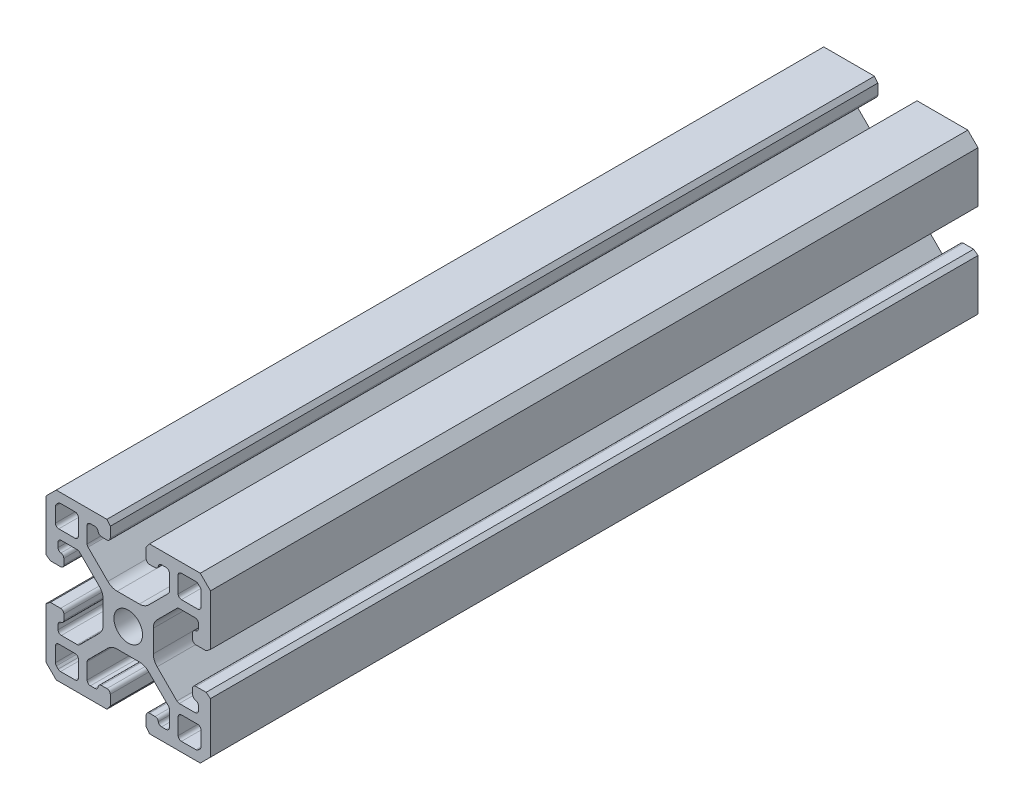
SolidWorks part; units mm, degrees
material "6063-T6"
ref_plane "Front Plane" through (0, 0, 0) normal (0, 0, 1) x (1, 0, 0)
ref_plane "Top Plane" through (0, 0, 0) normal (0, 1, 0) x (1, 0, 0)
ref_plane "Right Plane" through (0, 0, 0) normal (1, 0, 0) x (0, 0, -1)
sketch "Sketch1" plane through (0, 0, 0) normal (0, 0, 1) x (-1, 0, 0)
  line L0 (19.05, 0) -> (-19.05, 0) construction
  line L1 (0, -19.05) -> (0, 19.05) construction
  line L2 (-19.05, 4.9276) -> (-19.05, 16.6878)
  line L3 (-18.044, 4.1656) -> (-19.05, 4.9276)
  line L4 (-15.6692, 4.1656) -> (-18.044, 4.1656)
  line L5 (-14.9297, 6.2238) -> (-14.9074, 4.9409)
  line L6 (-16.256, 8.763) -> (-16.256, 7.7216)
  line L7 (-16.256, -7.7216) -> (-16.256, -8.763)
  line L8 (-14.9074, -4.9409) -> (-14.9297, -6.2238)
  line L9 (-18.044, -4.1656) -> (-15.6692, -4.1656)
  line L10 (-19.05, -4.9276) -> (-18.044, -4.1656)
  line L11 (-19.05, -16.6878) -> (-19.05, -4.9276)
  line L26 (-16.8656, 12.319) -> (-16.8656, 15.6829)
  line L27 (-16.6424, 16.2217) -> (-16.2217, 16.6424)
  line L28 (-15.6829, 16.8656) -> (-12.319, 16.8656)
  line L29 (-11.557, 16.1036) -> (-11.557, 12.319)
  line L30 (-12.319, 11.557) -> (-16.1036, 11.557)
  line L31 (-6.7001, -4.7245) -> (-11.2775, -9.3018)
  line L32 (-11.8163, -9.525) -> (-15.494, -9.525)
  line L34 (-15.494, 9.525) -> (-11.8163, 9.525)
  line L35 (-11.2775, 9.3018) -> (-6.7001, 4.7245)
  line L36 (-5.8074, 2.5692) -> (-5.8074, -2.5692)
  line L37 (-16.1036, -11.557) -> (-12.319, -11.557)
  line L38 (-11.557, -12.319) -> (-11.557, -16.1036)
  line L39 (-12.319, -16.8656) -> (-15.6829, -16.8656)
  line L40 (-16.2217, -16.6424) -> (-16.6424, -16.2217)
  line L41 (-16.8656, -15.6829) -> (-16.8656, -12.319)
  line L42 (15.6829, -16.8656) -> (12.319, -16.8656)
  line L43 (11.557, -16.1036) -> (11.557, -12.319)
  line L44 (12.319, -11.557) -> (16.1036, -11.557)
  line L45 (16.8656, -12.319) -> (16.8656, -15.6829)
  line L46 (16.6424, -16.2217) -> (16.2217, -16.6424)
  line L47 (11.557, 12.319) -> (11.557, 16.1036)
  line L48 (12.319, 16.8656) -> (15.6829, 16.8656)
  line L49 (16.2217, 16.6424) -> (16.6424, 16.2217)
  line L100 (5.8074, -2.5692) -> (5.8074, 2.5692)
  line L101 (6.7001, 4.7245) -> (11.2775, 9.3018)
  line L102 (11.8163, 9.525) -> (15.494, 9.525)
  line L103 (16.256, 8.763) -> (16.256, 7.7216)
  line L104 (14.9297, 6.2238) -> (14.9074, 4.9409)
  line L105 (15.6692, 4.1656) -> (18.044, 4.1656)
  line L106 (18.044, 4.1656) -> (19.05, 4.9276)
  line L107 (19.05, 4.9276) -> (19.05, 16.6878)
  line L108 (19.05, 16.6878) -> (16.6878, 19.05)
  line L109 (16.6878, 19.05) -> (4.9276, 19.05)
  line L110 (4.9276, 19.05) -> (4.1656, 18.044)
  line L111 (4.1656, 18.044) -> (4.1656, 15.6692)
  line L112 (4.9409, 14.9074) -> (6.2238, 14.9297)
  line L113 (7.7216, 16.256) -> (8.763, 16.256)
  line L114 (9.525, 15.494) -> (9.525, 11.8163)
  line L115 (9.3018, 11.2775) -> (4.7245, 6.7001)
  line L116 (2.5692, 5.8074) -> (-2.5692, 5.8074)
  line L117 (-4.7245, 6.7001) -> (-9.3018, 11.2775)
  line L118 (-9.525, 11.8163) -> (-9.525, 15.494)
  line L119 (-8.763, 16.256) -> (-7.7216, 16.256)
  line L120 (-6.2238, 14.9297) -> (-4.9409, 14.9074)
  line L121 (-4.1656, 15.6692) -> (-4.1656, 18.044)
  line L122 (-4.1656, 18.044) -> (-4.9276, 19.05)
  line L123 (-4.9276, 19.05) -> (-16.6878, 19.05)
  line L124 (-16.6878, 19.05) -> (-19.05, 16.6878)
  line L126 (-19.05, -16.6878) -> (-16.6878, -19.05)
  line L127 (-16.6878, -19.05) -> (-4.9276, -19.05)
  line L128 (-4.9276, -19.05) -> (-4.1656, -18.044)
  line L129 (-4.1656, -18.044) -> (-4.1656, -15.6692)
  line L130 (-4.9409, -14.9074) -> (-6.2238, -14.9297)
  line L131 (-7.7216, -16.256) -> (-8.763, -16.256)
  line L132 (-9.525, -15.494) -> (-9.525, -11.8163)
  line L133 (-9.3018, -11.2775) -> (-4.7245, -6.7001)
  line L134 (-2.5692, -5.8074) -> (2.5692, -5.8074)
  line L135 (4.7245, -6.7001) -> (9.3018, -11.2775)
  line L136 (9.525, -11.8163) -> (9.525, -15.494)
  line L137 (8.763, -16.256) -> (7.7216, -16.256)
  line L138 (6.2238, -14.9297) -> (4.9409, -14.9074)
  line L139 (4.1656, -15.6692) -> (4.1656, -18.044)
  line L140 (4.1656, -18.044) -> (4.9409, -19.05)
  line L141 (4.9409, -19.05) -> (16.6878, -19.05)
  line L142 (16.6878, -19.05) -> (19.05, -16.6878)
  line L143 (19.05, -16.6878) -> (19.05, -4.9276)
  line L144 (19.05, -4.9276) -> (18.044, -4.1656)
  line L145 (18.044, -4.1656) -> (15.6692, -4.1656)
  line L146 (14.9074, -4.9409) -> (14.9297, -6.2238)
  line L147 (16.256, -7.7216) -> (16.256, -8.763)
  line L148 (15.494, -9.525) -> (11.8163, -9.525)
  line L149 (11.2775, -9.3018) -> (6.7001, -4.7245)
  line L150 (16.8656, 15.6829) -> (16.8656, 12.319)
  line L151 (16.1036, 11.557) -> (12.319, 11.557)
  arc A0 (-16.256, 8.763) -> (-15.494, 9.525) centre (-15.494, 8.763) cw
  arc A1 (-14.9074, 4.9409) -> (-15.6692, 4.1656) centre (-15.6692, 4.9276) cw
  arc A2 (-15.5928, 6.966) -> (-14.9297, 6.2238) centre (-15.6916, 6.2105) cw
  arc A3 (-15.5928, 6.966) -> (-16.256, 7.7216) centre (-15.494, 7.7216) cw
  arc A4 (-15.494, -9.525) -> (-16.256, -8.763) centre (-15.494, -8.763) cw
  arc A5 (-16.256, -7.7216) -> (-15.5928, -6.966) centre (-15.494, -7.7216) cw
  arc A6 (-14.9297, -6.2238) -> (-15.5928, -6.966) centre (-15.6916, -6.2105) cw
  arc A7 (-15.6692, -4.1656) -> (-14.9074, -4.9409) centre (-15.6692, -4.9276) cw
  arc A27 (-16.6424, 16.2217) -> (-16.8656, 15.6829) centre (-16.1036, 15.6829) ccw
  arc A28 (-15.6829, 16.8656) -> (-16.2217, 16.6424) centre (-15.6829, 16.1036) ccw
  arc A29 (-11.557, 16.1036) -> (-12.319, 16.8656) centre (-12.319, 16.1036) ccw
  arc A30 (-12.319, 11.557) -> (-11.557, 12.319) centre (-12.319, 12.319) ccw
  arc A31 (-16.8656, 12.319) -> (-16.1036, 11.557) centre (-16.1036, 12.319) ccw
  arc A32 (-11.8163, -9.525) -> (-11.2775, -9.3018) centre (-11.8163, -8.763) ccw
  arc A35 (-11.2775, 9.3018) -> (-11.8163, 9.525) centre (-11.8163, 8.763) ccw
  arc A72 (5.8074, -2.5692) -> (6.7001, -4.7245) centre (8.8554, -2.5692) ccw
  arc A73 (6.7001, 4.7245) -> (5.8074, 2.5692) centre (8.8554, 2.5692) ccw
  arc A74 (11.8163, 9.525) -> (11.2775, 9.3018) centre (11.8163, 8.763) ccw
  arc A75 (16.256, 8.763) -> (15.494, 9.525) centre (15.494, 8.763) ccw
  arc A76 (15.5928, 6.966) -> (16.256, 7.7216) centre (15.494, 7.7216) ccw
  arc A77 (15.5928, 6.966) -> (14.9297, 6.2238) centre (15.6916, 6.2105) ccw
  arc A78 (14.9074, 4.9409) -> (15.6692, 4.1656) centre (15.6692, 4.9276) ccw
  arc A79 (4.1656, 15.6692) -> (4.9409, 14.9074) centre (4.9276, 15.6692) ccw
  arc A80 (6.2238, 14.9297) -> (6.966, 15.5928) centre (6.2105, 15.6916) ccw
  arc A81 (7.7216, 16.256) -> (6.966, 15.5928) centre (7.7216, 15.494) ccw
  arc A82 (9.525, 15.494) -> (8.763, 16.256) centre (8.763, 15.494) ccw
  arc A83 (9.3018, 11.2775) -> (9.525, 11.8163) centre (8.763, 11.8163) ccw
  arc A84 (2.5692, 5.8074) -> (4.7245, 6.7001) centre (2.5692, 8.8554) ccw
  arc A85 (-4.7245, 6.7001) -> (-2.5692, 5.8074) centre (-2.5692, 8.8554) ccw
  arc A86 (-9.525, 11.8163) -> (-9.3018, 11.2775) centre (-8.763, 11.8163) ccw
  arc A87 (-8.763, 16.256) -> (-9.525, 15.494) centre (-8.763, 15.494) ccw
  arc A88 (-6.966, 15.5928) -> (-7.7216, 16.256) centre (-7.7216, 15.494) ccw
  arc A89 (-6.966, 15.5928) -> (-6.2238, 14.9297) centre (-6.2105, 15.6916) ccw
  arc A90 (-4.9409, 14.9074) -> (-4.1656, 15.6692) centre (-4.9276, 15.6692) ccw
  arc A91 (-4.1656, -15.6692) -> (-4.9409, -14.9074) centre (-4.9276, -15.6692) ccw
  arc A92 (-6.2238, -14.9297) -> (-6.966, -15.5928) centre (-6.2105, -15.6916) ccw
  arc A93 (-7.7216, -16.256) -> (-6.966, -15.5928) centre (-7.7216, -15.494) ccw
  arc A94 (-9.525, -15.494) -> (-8.763, -16.256) centre (-8.763, -15.494) ccw
  arc A95 (-9.3018, -11.2775) -> (-9.525, -11.8163) centre (-8.763, -11.8163) ccw
  arc A96 (-2.5692, -5.8074) -> (-4.7245, -6.7001) centre (-2.5692, -8.8554) ccw
  arc A97 (4.7245, -6.7001) -> (2.5692, -5.8074) centre (2.5692, -8.8554) ccw
  arc A98 (9.525, -11.8163) -> (9.3018, -11.2775) centre (8.763, -11.8163) ccw
  arc A99 (8.763, -16.256) -> (9.525, -15.494) centre (8.763, -15.494) ccw
  arc A100 (6.966, -15.5928) -> (7.7216, -16.256) centre (7.7216, -15.494) ccw
  arc A101 (6.966, -15.5928) -> (6.2238, -14.9297) centre (6.2105, -15.6916) ccw
  arc A102 (4.9409, -14.9074) -> (4.1656, -15.6692) centre (4.9276, -15.6692) ccw
  arc A103 (15.6692, -4.1656) -> (14.9074, -4.9409) centre (15.6692, -4.9276) ccw
  arc A104 (14.9297, -6.2238) -> (15.5928, -6.966) centre (15.6916, -6.2105) ccw
  arc A105 (16.256, -7.7216) -> (15.5928, -6.966) centre (15.494, -7.7216) ccw
  arc A106 (15.494, -9.525) -> (16.256, -8.763) centre (15.494, -8.763) ccw
  arc A107 (11.2775, -9.3018) -> (11.8163, -9.525) centre (11.8163, -8.763) ccw
  arc A108 (-5.8074, 2.5692) -> (-6.7001, 4.7245) centre (-8.8554, 2.5692) ccw
  arc A109 (-6.7001, -4.7245) -> (-5.8074, -2.5692) centre (-8.8554, -2.5692) ccw
  arc A110 (-11.557, -12.319) -> (-12.319, -11.557) centre (-12.319, -12.319) ccw
  arc A111 (-12.319, -16.8656) -> (-11.557, -16.1036) centre (-12.319, -16.1036) ccw
  arc A112 (-16.2217, -16.6424) -> (-15.6829, -16.8656) centre (-15.6829, -16.1036) ccw
  arc A113 (-16.8656, -15.6829) -> (-16.6424, -16.2217) centre (-16.1036, -15.6829) ccw
  arc A114 (-16.1036, -11.557) -> (-16.8656, -12.319) centre (-16.1036, -12.319) ccw
  circle A115 centre (0, 0) radius 3.3147
  arc A116 (11.557, -16.1036) -> (12.319, -16.8656) centre (12.319, -16.1036) ccw
  arc A117 (12.319, -11.557) -> (11.557, -12.319) centre (12.319, -12.319) ccw
  arc A118 (16.8656, -12.319) -> (16.1036, -11.557) centre (16.1036, -12.319) ccw
  arc A119 (16.6424, -16.2217) -> (16.8656, -15.6829) centre (16.1036, -15.6829) ccw
  arc A120 (15.6829, -16.8656) -> (16.2217, -16.6424) centre (15.6829, -16.1036) ccw
  arc A121 (12.319, 16.8656) -> (11.557, 16.1036) centre (12.319, 16.1036) ccw
  arc A122 (16.2217, 16.6424) -> (15.6829, 16.8656) centre (15.6829, 16.1036) ccw
  arc A123 (16.8656, 15.6829) -> (16.6424, 16.2217) centre (16.1036, 15.6829) ccw
  arc A124 (16.1036, 11.557) -> (16.8656, 12.319) centre (16.1036, 12.319) ccw
  arc A125 (11.557, 12.319) -> (12.319, 11.557) centre (12.319, 12.319) ccw
  dimension "D1" = 6.6294
  dimension "D2" = 38.1
  dimension "D3" = 38.1
extrude "Boss-Extrude1" add sketch "Sketch1" along normal blind 177.8
